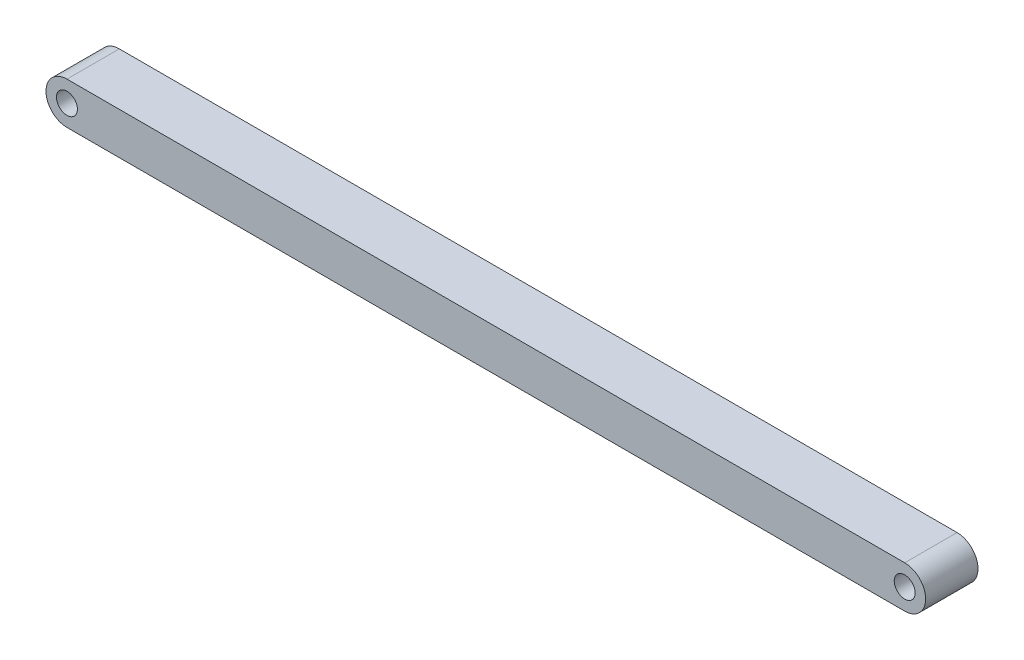
SolidWorks part; units mm, degrees
ref_plane "前视基准面" through (0, 0, 0) normal (0, 0, 1) x (1, 0, 0)
ref_plane "上视基准面" through (0, 0, 0) normal (0, 1, 0) x (1, 0, 0)
ref_plane "右视基准面" through (0, 0, 0) normal (1, 0, 0) x (0, 0, -1)
sketch "草图2" plane through (0, 0, 0) normal (0, 0, 1) x (1, 0, 0)
  line L0 (0, -2) -> (80, -2)
  line L1 (80, 2) -> (0, 2)
  circle A0 centre (0, 0) radius 2
  circle A1 centre (80, 0) radius 2
  circle A2 centre (0, 0) radius 1
  circle A3 centre (80, 0) radius 1
  point P11 (80, 0)
  dimension "D1" = 4
  dimension "D3" = 4
  dimension "D4" = 2
  dimension "D5" = 2
  dimension "D2" = 80
extrude "凸台-拉伸1" add sketch "草图2" along normal blind 5 contours A0 A2 | A1 L1 A0 L0 | A1 A3
